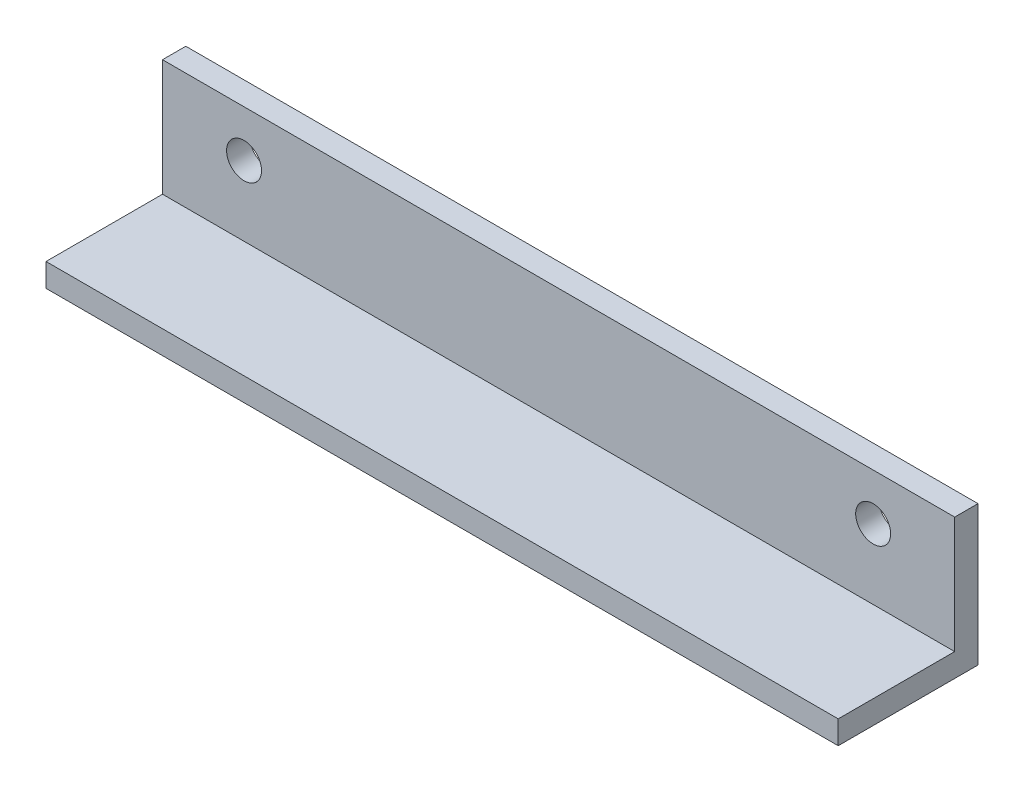
SolidWorks part; units mm, degrees
material "6063-O"
ref_plane "Front Plane" through (0, 0, 0) normal (0, 0, 1) x (1, 0, 0)
ref_plane "Top Plane" through (0, 0, 0) normal (0, 1, 0) x (1, 0, 0)
ref_plane "Right Plane" through (0, 0, 0) normal (1, 0, 0) x (0, 0, -1)
sketch "Sketch1" plane through (0, 0, 0) normal (1, 0, 0) x (0, 0, -1)
  line L0 (-38.1, 0) -> (0, 0)
  line L1 (55, 0) -> (-55, 0) construction
  line L2 (0, 0) -> (0, 38.1)
  line L3 (0, 55) -> (0, -55) construction
  dimension "D1" = 38.1
  dimension "D2" = 38.1
extrude "Extrude-Thin1" add sketch "Sketch1" along normal mid plane 215.9 thin thin type one direction reverse wall 6.35
hole_wizard "#10 Clearance Hole1" positions "Sketch2" profile "Sketch3" hole size "#10" standard "ANSI Inch"
sketch "Sketch2" plane through (0, 3.175, 0) normal (0, 1, 0) x (1, 0, 0)
  line L0 (127, -38.1) -> (-127, -38.1) construction
  line L1 (0, -20.955) -> (0, 20.955) construction
  point P0 (-114.3, -15.875)
  point P2 (-114.3, -28.575)
  point P4 (-88.9, -28.575)
  point P6 (-88.9, -15.875)
  point P8 (88.9, -15.875)
  point P10 (88.9, -28.575)
  point P12 (114.3, -28.575)
  point P14 (114.3, -15.875)
  dimension "D1" = 9.525
  dimension "D2" = 12.7
  dimension "D3" = 114.3
  dimension "D4" = 25.4
  dimension "D5" = 114.3
  dimension "D6" = 25.4
sketch "Sketch3" plane through (-114.3, 3.175, 15.875) normal (1, 0, 0) x (0, 0, 1)
  line L0 (0, 0) -> (0, 3.175)
  line L1 (0, 3.175) -> (2.667, 3.175)
  line L2 (2.667, 3.175) -> (2.667, 0)
  line L5 (2.667, 0) -> (0, 0)
  line L11 (0, -6.35) -> (0, 107.95) construction
  dimension "Thru Hole Dia." = 5.334
  dimension "Thru Hole Depth" = 3.175
hole_wizard "3/8 (0.375) Diameter Hole1" positions "Sketch4" profile "Sketch5" hole size "3/8" standard "ANSI Inch" end condition up to next
sketch "Sketch4" plane through (0, 0, 6.35) normal (0, 0, 1) x (1, 0, 0)
  line L0 (107.95, 38.1) -> (-107.95, 38.1) construction
  line L1 (0, -20.955) -> (0, 20.955) construction
  point P0 (-85.725, 25.4)
  point P2 (85.725, 25.4)
  dimension "D1" = 12.7
  dimension "D2" = 171.45
  dimension "D3" = 85.725
sketch "Sketch5" plane through (-85.725, 25.4, 6.35) normal (1, 0, 0) x (0, -1, 0)
  line L0 (0, 0) -> (0, 6.35)
  line L1 (0, 6.35) -> (4.7625, 6.35)
  line L2 (4.7625, 6.35) -> (4.7625, 0)
  line L5 (4.7625, 0) -> (0, 0)
  line L11 (0, -6.35) -> (0, 107.95) construction
  dimension "Thru Hole Dia." = 9.525
  dimension "Thru Hole Depth" = 6.35
